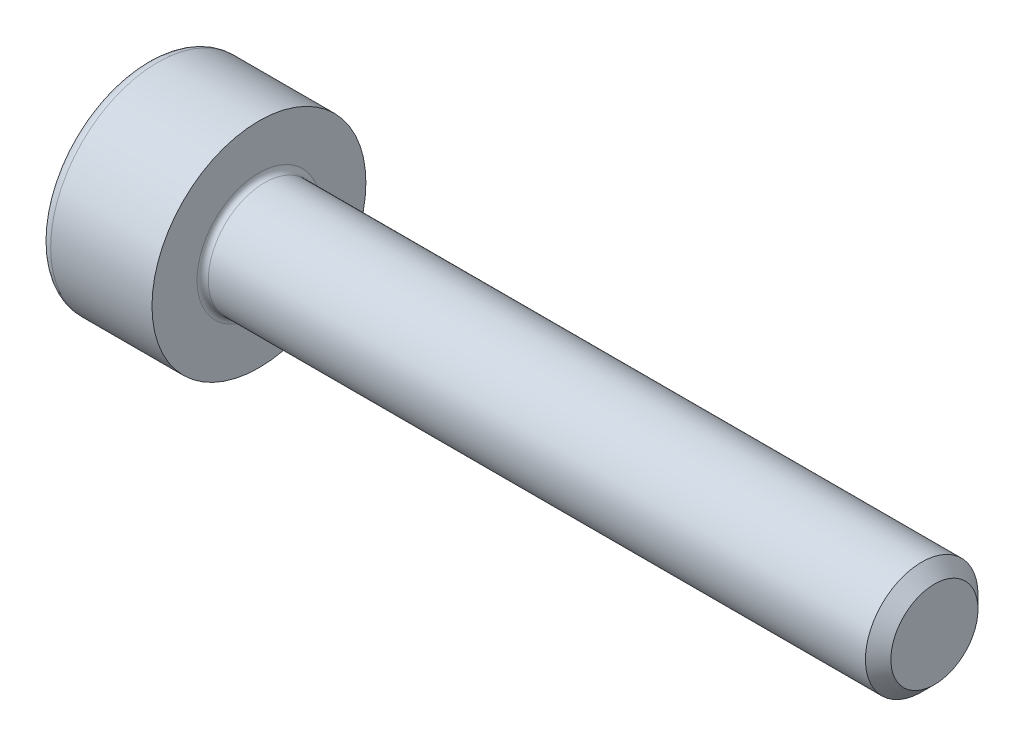
SolidWorks part; units mm, degrees
ref_plane "Спереди" through (0, 0, 0) normal (0, 0, 1) x (1, 0, 0)
ref_plane "Сверху" through (0, 0, 0) normal (0, 1, 0) x (1, 0, 0)
ref_plane "Справа" through (0, 0, 0) normal (1, 0, 0) x (0, 0, -1)
ref_plane "Плоскость4" through (0, 0, 0) normal (0, 0, -1) x (-1, 0, 0)
sketch "Эскиз1" plane through (0, 0, 0) normal (0, 0, -1) x (-1, 0, 0)
  line L0 (-2, 1.9) -> (-2, 0)
  line L1 (-2, 0) -> (0, 0)
  line L2 (0, 0) -> (0, 1.9)
  line L3 (0, 1.9) -> (-2, 1.9)
  line L4 (-2, 0) -> (0, 0) construction
revolve "Повернуть1" add sketch "Эскиз1" angle 360 about L4
sketch "Эскиз2" plane through (2, 0, 0) normal (1, 0, 0) x (0, 0, -1)
  circle A0 centre (0, 0) radius 1
extrude "Бобышка-Вытянуть1" add sketch "Эскиз2" along normal blind 12
sketch "Эскиз3" plane through (0, 0, 0) normal (-1, 0, 0) x (0, 0, 1)
  line L0 (-0.76, -0.4388) -> (0, -0.8776)
  line L1 (0, -0.8776) -> (0.76, -0.4388)
  line L2 (0.76, -0.4388) -> (0.76, 0.4388)
  line L3 (0.76, 0.4388) -> (0, 0.8776)
  line L4 (0, 0.8776) -> (-0.76, 0.4388)
  line L5 (-0.76, 0.4388) -> (-0.76, -0.4388)
extrude "Вырез-Вытянуть1" cut sketch "Эскиз3" against normal blind 1
sketch "Эскиз4" plane through (0, 0, 0) normal (0, 0, 1) x (1, 0, 0)
  line L0 (1, 0.76) -> (1, 0)
  line L1 (1, 0) -> (1.4388, 0)
  line L2 (1.4388, 0) -> (1, 0.76)
  line L3 (1, 0) -> (1.4389, 0) construction
revolve "Вырез-Повернуть1" cut sketch "Эскиз4" angle 360 about L3
chamfer "Фаска1" distance 0.226 angle 45 1 edges at (14, 0, -1)
fillet "Скругление1" radius 0.1 1 edges at (2, 0, -1)
fillet "Скругление2" radius 0.2 1 edges at (0, 0, 1.9)
